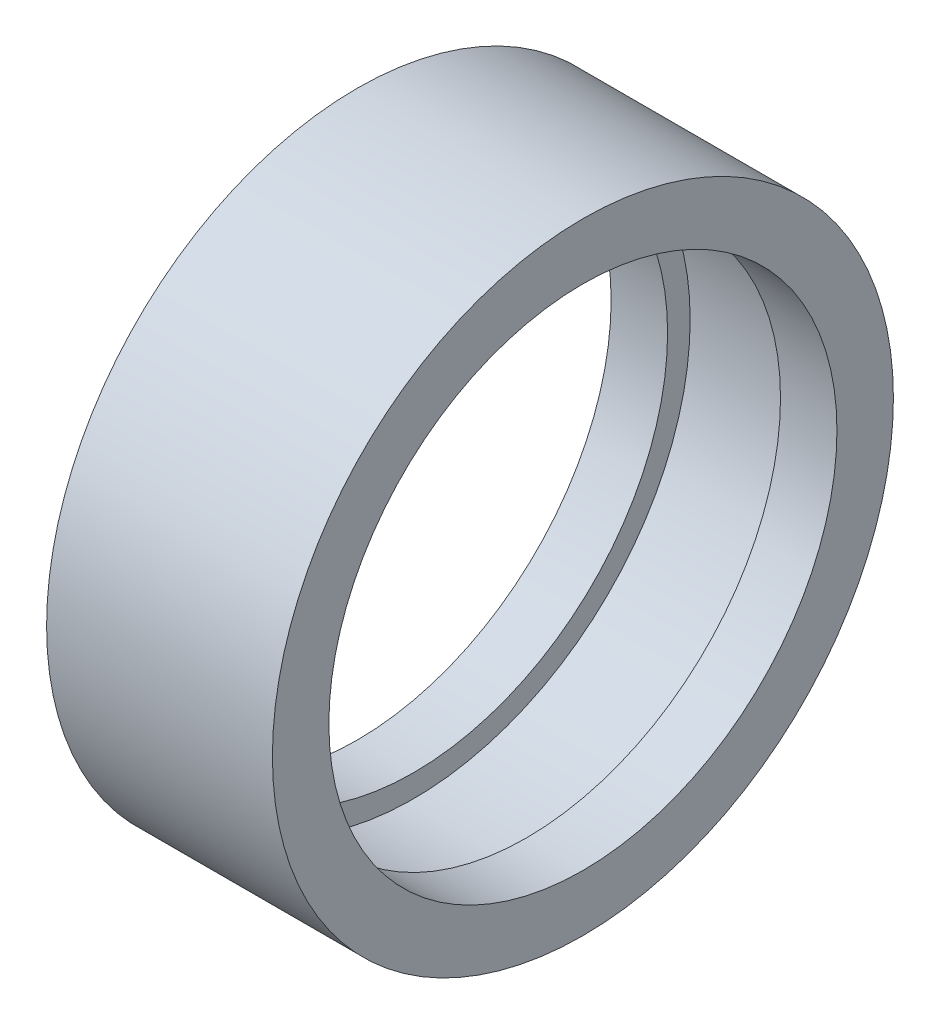
SolidWorks part; units mm, degrees
ref_plane "Front Plane" through (0, 0, 0) normal (0, 0, 1) x (1, 0, 0)
ref_plane "Top Plane" through (0, 0, 0) normal (0, 1, 0) x (1, 0, 0)
ref_plane "Right Plane" through (0, 0, 0) normal (1, 0, 0) x (0, 0, -1)
sketch "Sketch1" plane through (0, 0, 0) normal (0, 0, 1) x (1, 0, 0)
  line L0 (0, 0) -> (-12.7713, 0) construction
  line L1 (-5.0224, 11) -> (2.9776, 11)
  line L2 (2.9776, 11) -> (2.9776, 9)
  line L3 (-5.0224, 11) -> (-5.0224, 9)
  line L4 (-5.0224, 9) -> (-3.0224, 9)
  line L5 (2.9776, 9) -> (0.9776, 9)
  line L6 (-3.0224, 9) -> (-3.0224, 9.8)
  line L7 (-3.0224, 9.8) -> (0.9776, 9.8)
  line L8 (0.9776, 9.8) -> (0.9776, 9)
  dimension "D1" = 8
  dimension "D2" = 2
  dimension "D3" = 11
  dimension "D4" = 2
  dimension "D5" = 2
  dimension "D6" = 2
  dimension "D7" = 0.8
revolve "Revolve1" add sketch "Sketch1" angle 360 about L0
